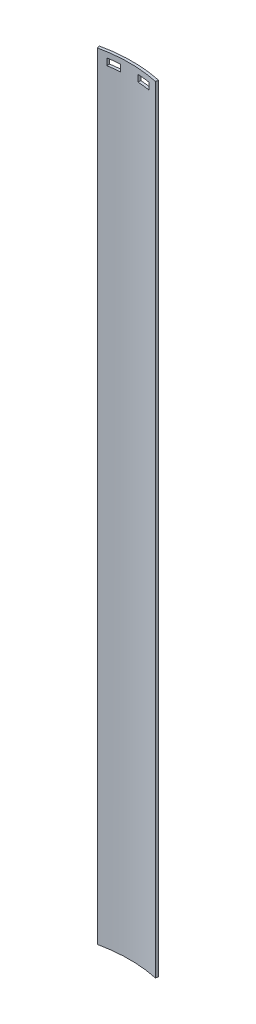
SolidWorks part; units mm, degrees
material "PVC 0.007 Plasticized"
ref_plane "Front Plane" through (0, 0, 0) normal (0, 0, 1) x (1, 0, 0)
ref_plane "Top Plane" through (0, 0, 0) normal (0, 1, 0) x (1, 0, 0)
ref_plane "Right Plane" through (0, 0, 0) normal (1, 0, 0) x (0, 0, -1)
sketch "Sketch3" plane through (0, 0, 0) normal (0, 1, 0) x (1, 0, 0)
  line L0 (-55, -0.0164) -> (-53.9423, -4.9033)
  line L1 (53.9423, -4.9033) -> (55, -0.0164)
  arc A0 (-55, -0.0164) -> (55, -0.0164) centre (0, -254.1325) cw
  arc A1 (-53.9423, -4.9033) -> (53.9423, -4.9033) centre (0, -254.1325) cw
  point P6 (0, 5.8675)
  dimension "D3" = 260
  dimension "D1" = 110
  dimension "D2" = 5
extrude "Boss-Extrude1" add sketch "Sketch3" along normal mid plane 1440
ref_plane "Plane1" through (-53.9423, 720, 4.9033) normal (0, -1, 0) x (-1, 0, 0)
sketch "Sketch8" plane through (0, 0, 0) normal (0, 0, 1) x (1, 0, 0)
  line L0 (0, 0) -> (0, 763.5585) construction
  line L1 (-53.9423, 720) -> (-53.9423, -720) construction
  line L2 (-16.4423, 710) -> (-38.9423, 710)
  line L3 (-16.4423, 710) -> (-16.4423, 697.5)
  line L4 (-16.4423, 697.5) -> (-38.9423, 697.5)
  line L5 (-38.9423, 710) -> (-38.9423, 697.5)
  line L6 (-16.4423, 710) -> (-38.9423, 697.5) construction
  line L7 (-16.4423, 697.5) -> (-38.9423, 710) construction
  line L8 (53.9423, 720) -> (-53.9423, 720) construction
  line L9 (16.4423, 710) -> (16.4423, 697.5)
  line L10 (16.4423, 697.5) -> (38.9423, 697.5)
  line L11 (38.9423, 710) -> (38.9423, 697.5)
  line L12 (16.4423, 710) -> (38.9423, 710)
  point P3 (-27.6923, 703.75)
  dimension "D1" = 15
  dimension "D2" = 12.5
  dimension "D3" = 10
  dimension "D4" = 22.5
extrude "Cut-Extrude6" cut sketch "Sketch8" against normal through all both and the other way through all
